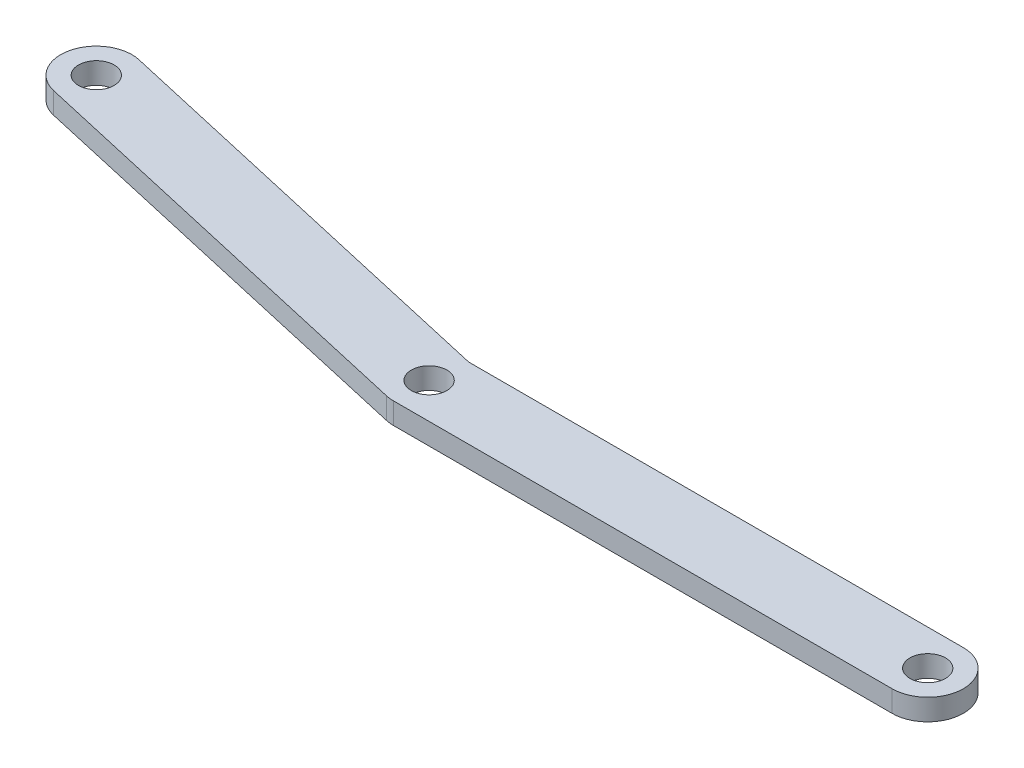
SolidWorks part; units mm, degrees
ref_plane "Front Plane" through (0, 0, 0) normal (0, 0, 1) x (1, 0, 0)
ref_plane "Top Plane" through (0, 0, 0) normal (0, 1, 0) x (1, 0, 0)
ref_plane "Right Plane" through (0, 0, 0) normal (1, 0, 0) x (0, 0, -1)
sketch "Sketch1" plane through (0, 0, 0) normal (0, 1, 0) x (1, 0, 0)
  line L0 (-44.45, 0) -> (44.45, 0) construction
  line L1 (-44.45, 6.35) -> (44.45, 6.35)
  line L2 (-44.45, -6.35) -> (44.45, -6.35)
  arc A0 (-44.45, 6.35) -> (-44.45, -6.35) centre (-44.45, 0) ccw
  arc A1 (44.45, -6.35) -> (44.45, 6.35) centre (44.45, 0) ccw
  circle A3 centre (44.45, 0) radius 3.175
  point P2 (0, 0)
  dimension "D2" = 6.35
  dimension "D4" = 6.35
  dimension "D1" = 88.9
sketch "Sketch2" plane through (0, 0, 0) normal (0, 1, 0) x (1, 0, 0)
  line L0 (-44.45, 0) -> (-121.2333, 17.4447) construction
  line L1 (-45.8568, -6.1922) -> (-122.6401, 11.2525)
  line L2 (-43.0432, 6.1922) -> (-119.8264, 23.6369)
  line L3 (-44.45, 0) -> (44.45, 0) construction
  arc A0 (-45.8568, -6.1922) -> (-43.0432, 6.1922) centre (-44.45, 0) ccw
  arc A1 (-119.8264, 23.6369) -> (-122.6401, 11.2525) centre (-121.2333, 17.4447) ccw
  circle A2 centre (-121.2333, 17.4447) radius 3.175
  point P3 (-82.8416, 8.7224)
  dimension "D3" = 6.35
  dimension "D4" = 6.35
  dimension "D1" = 167.2
  dimension "D2" = 78.74
extrude "Boss-Extrude2" add sketch "Sketch2" along normal blind 3.81
extrude "Boss-Extrude3" add sketch "Sketch1" along normal blind 3.81
sketch "Sketch3" plane through (0, 3.81, 0) normal (0, 1, 0) x (1, 0, 0)
  circle A0 centre (-44.45, 0) radius 3.175
  dimension "D1" = 6.35
extrude "Cut-Extrude1" cut sketch "Sketch3" against normal through all both and the other way through all
